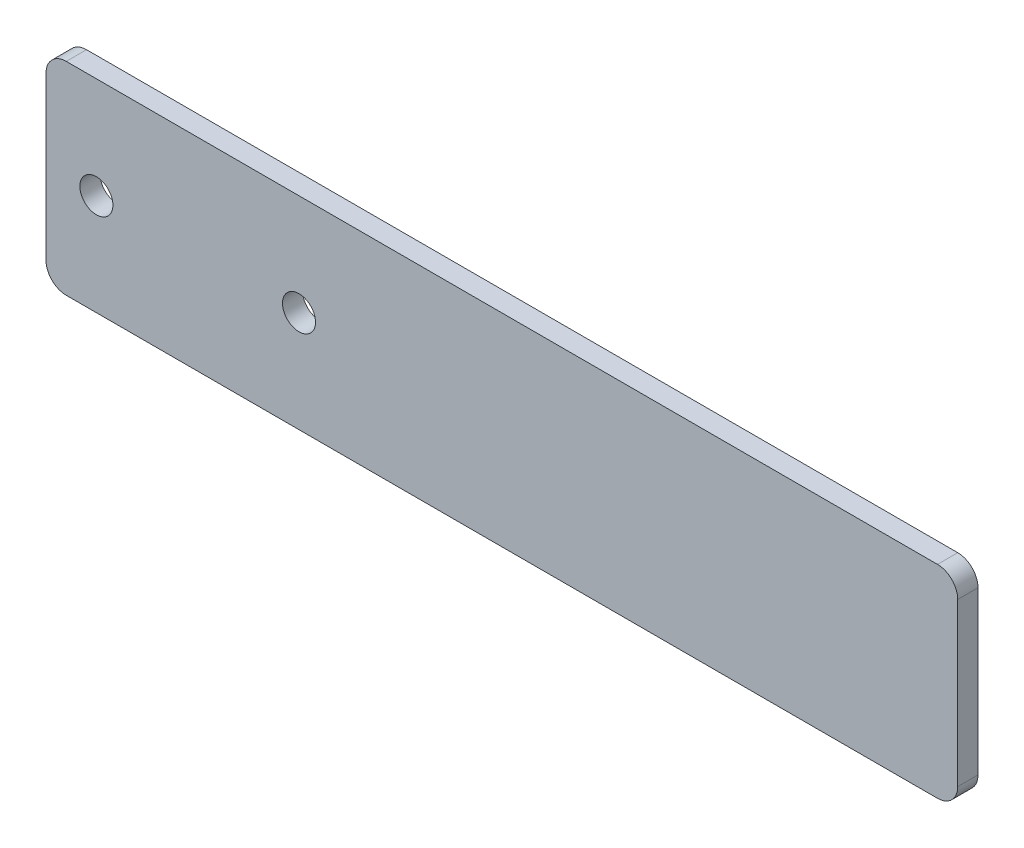
SolidWorks part; units mm, degrees
ref_plane "Front" through (0, 0, 0) normal (0, 0, 1) x (1, 0, 0)
ref_plane "Top" through (0, 0, 0) normal (0, 1, 0) x (1, 0, 0)
ref_plane "Right" through (0, 0, 0) normal (1, 0, 0) x (0, 0, -1)
sketch "Sketch1" plane through (0, 0, 0) normal (0, 0, 1) x (1, 0, 0)
  line L9 (1628.4479, 202.5965) -> (1628.4479, 177.1965)
  line L10 (1628.4479, 177.1965) -> (1514.1479, 177.1965)
  line L11 (1514.1479, 177.1965) -> (1514.1479, 202.5965)
  line L13 (1514.1479, 202.5965) -> (1628.4479, 202.5965)
  circle A0 centre (1545.8653, 189.8965) radius 2.0701
  arc A1 (1547.934, 189.9727) -> (1543.7966, 189.9727) centre (1545.8653, 189.8965) ccw construction
  circle A2 centre (1520.4653, 189.8965) radius 2.0701
  arc A3 (1522.534, 189.9727) -> (1518.3966, 189.9727) centre (1520.4653, 189.8965) ccw construction
  point P0 (0, 0)
  point P1 (0, 0)
  dimension "D1" = 25.4
  dimension "D2" = 114.3
extrude "Boss-Extrude1" add sketch "Sketch1" along normal blind 2.54
fillet "Fillet1" radius 2.54 4 edges at (1628.4479, 177.1965, 1.27) (1628.4479, 202.5965, 1.27) (1514.1479, 202.5965, 1.27) (1514.1479, 177.1965, 1.27)
sketch "Bend-Lines1" [suppressed] plane through (0, 0, 0) normal (0, 1, 0) x (1, 0, 0)
sketch "Bounding-Box1" [suppressed] plane through (0, 0, 0) normal (0, 1, 0) x (1, 0, 0)
